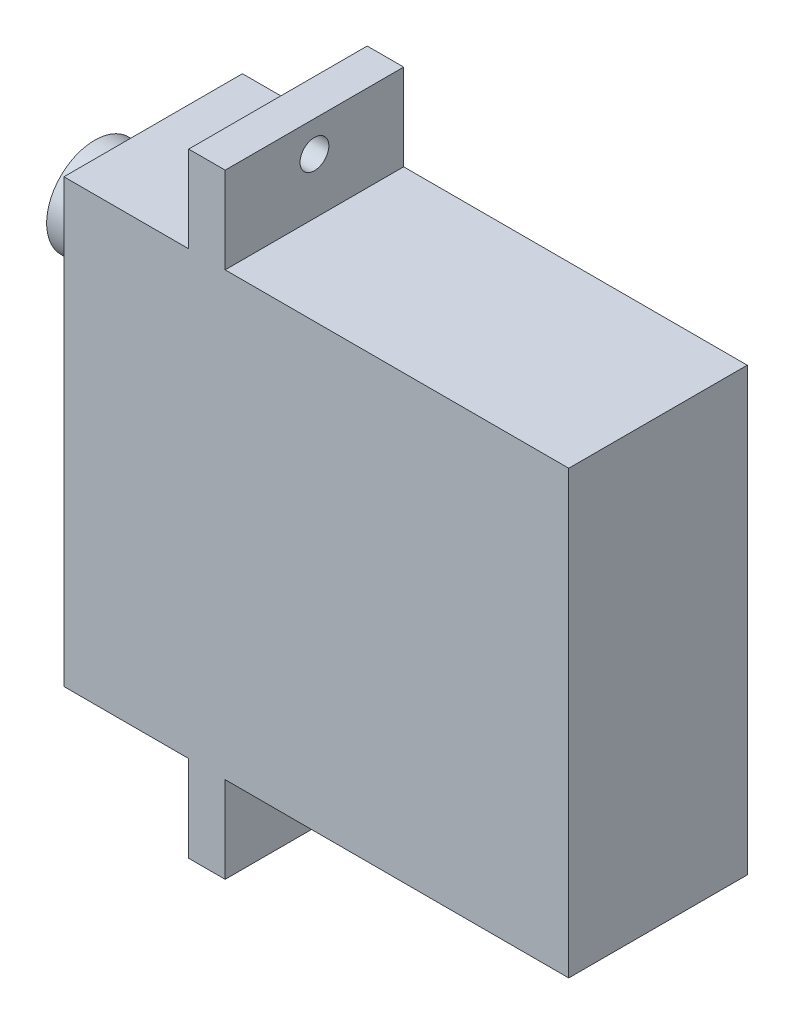
SolidWorks part; units mm, degrees
ref_plane "Front Plane" through (0, 0, 0) normal (0, 0, 1) x (1, 0, 0)
ref_plane "Top Plane" through (0, 0, 0) normal (0, 1, 0) x (1, 0, 0)
ref_plane "Right Plane" through (0, 0, 0) normal (1, 0, 0) x (0, 0, -1)
sketch "Sketch1" plane through (0, 0, 0) normal (0, 0, 1) x (1, 0, 0)
  line L0 (-4.75, 11.5) -> (-4.75, 16)
  line L1 (-13.15, -11.5) -> (-6.65, -11.5)
  line L2 (-13.15, -11.5) -> (-13.15, 11.5)
  line L3 (-13.15, 11.5) -> (-6.65, 11.5)
  line L4 (13.15, -11.5) -> (13.15, 11.5)
  line L5 (-13.15, -11.5) -> (13.15, 11.5) construction
  line L6 (-13.15, 11.5) -> (13.15, -11.5) construction
  line L7 (-4.75, 16) -> (-6.65, 16)
  line L8 (-6.65, 16) -> (-6.65, 11.5)
  line L9 (-4.75, 11.5) -> (13.15, 11.5)
  line L10 (-4.75, -11.5) -> (-4.75, -16)
  line L11 (-4.75, -16) -> (-6.65, -16)
  line L12 (-6.65, -16) -> (-6.65, -11.5)
  line L13 (-4.75, -11.5) -> (13.15, -11.5)
  point P0 (0, 0)
  dimension "D1" = 26.3
  dimension "D2" = 23
  dimension "D3" = 32
  dimension "D4" = 6.5
  dimension "D5" = 1.9
extrude "Boss-Extrude1" add sketch "Sketch1" along normal mid plane 9.3
sketch "Sketch2" plane through (-13.15, 0, 0) normal (-1, 0, 0) x (0, 0, 1)
  line L0 (0, 11.5) -> (0, 6.8) construction
  line L2 (4.65, 11.5) -> (-4.65, 11.5) construction
  circle A0 centre (0, 6.8) radius 2.5
  dimension "D1" = 5
  dimension "D2" = 4.7
sketch "Sketch3" plane through (0, 0, 0) normal (0, 0, 1) x (1, 0, 0)
  line L0 (-13.15, 6.8) -> (-16.2, 6.8)
  line L1 (-16.2, 6.8) -> (-16.2, 9.3)
  line L6 (-16.2, 9.3) -> (-13.15, 9.3)
  line L7 (-13.15, 11.5) -> (-13.15, 6.8) construction
  line L8 (-13.15, 9.3) -> (-13.15, 6.8)
  line L9 (-13.15, 11.5) -> (-13.15, -11.5) construction
  dimension "D2" = 2.5
  dimension "D5" = 3.05
revolve "Revolve1" add sketch "Sketch3" angle 360 about L0
sketch "Sketch4" plane through (-6.65, 0, 0) normal (-1, 0, 0) x (0, 0, 1)
  line L0 (0, 16) -> (0, 14.4) construction
  line L1 (4.65, 16) -> (-4.65, 16) construction
  line L2 (0, 14.4) -> (0, -14.4) construction
  line L3 (0, -14.4) -> (0, -16) construction
  line L4 (4.65, -16) -> (-4.65, -16) construction
  circle A0 centre (0, 14.4) radius 0.75
  circle A1 centre (0, -14.4) radius 0.75
  dimension "D1" = 1.5
  dimension "D2" = 1.6
extrude "Cut-Extrude1" cut sketch "Sketch4" against normal blind 10
sketch "Sketch5" [suppressed] plane through (-17.75, 0, 0) normal (-1, 0, 0) x (0, 0, 1)
  line L0 (-9.3675, 10.3) -> (9.3675, 10.3)
  circle A0 centre (0, 6.8) radius 3.5 construction
  circle A1 centre (0, 6.8) radius 10
  arc A2 (9.3675, 10.3) -> (-9.3675, 10.3) centre (0, 6.8) ccw
  circle A3 centre (0, 6.8) radius 3.5 construction
  dimension "D1" = 0
extrude "Cut-Extrude2" [suppressed] cut sketch "Sketch5" against normal up to surface (1.7 mm away)
sketch "Sketch6" [suppressed] plane through (-17.75, 0, 0) normal (-1, 0, 0) x (0, 0, 1)
  line L0 (9.3675, 3.3) -> (-9.3675, 3.3)
  circle A0 centre (0, 6.8) radius 3.5 construction
  circle A1 centre (0, 6.8) radius 10
  arc A2 (-9.3675, 3.3) -> (9.3675, 3.3) centre (0, 6.8) ccw
  circle A3 centre (0, 6.8) radius 3.5 construction
  dimension "D1" = 0
extrude "Cut-Extrude3" [suppressed] cut sketch "Sketch6" against normal up to next
surface "Surface-Offset1" [suppressed] parameters "D1"=0.2
surface "Surface-Extend2" [suppressed] parameters "D1"=2.4
surface "Surface-Plane1" [suppressed]
surface "Surface-Knit1" [suppressed]
surface "Surface-Fill1" [suppressed]
surface "Surface-Fill2" [suppressed]
surface "Surface-Fill3" [suppressed]
surface "Surface-Fill4" [suppressed]
surface "Surface-Fill5" [suppressed]
surface "Surface-Knit2" [suppressed]
